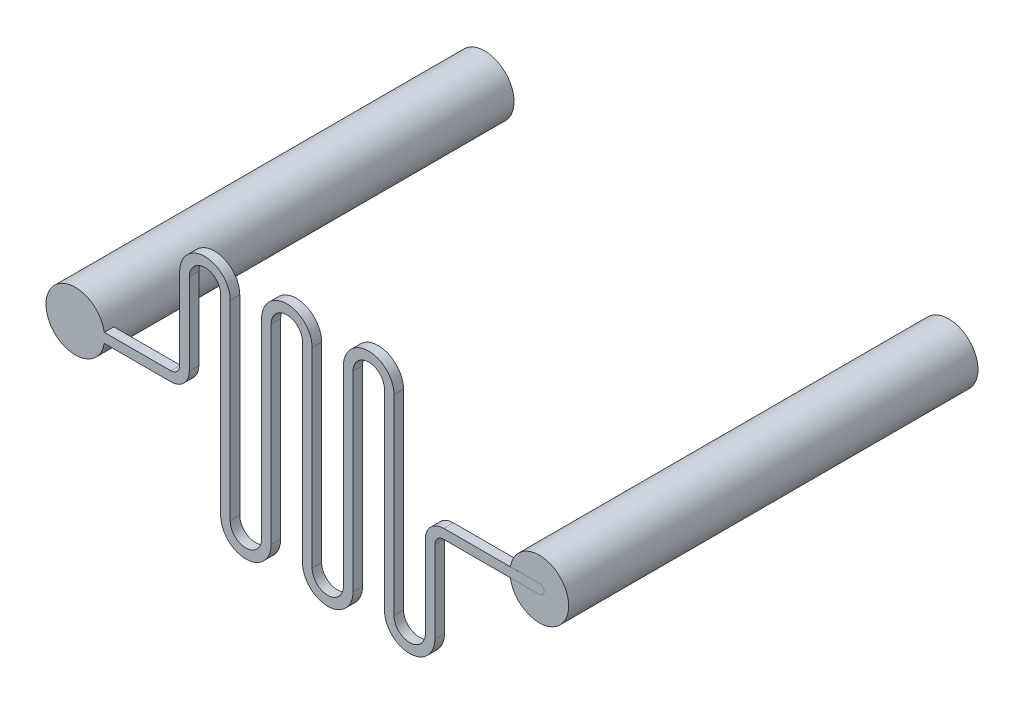
SolidWorks part; units mm, degrees
ref_plane "Front Plane" through (0, 0, 0) normal (0, 0, 1) x (1, 0, 0)
ref_plane "Top Plane" through (0, 0, 0) normal (0, 1, 0) x (1, 0, 0)
ref_plane "Right Plane" through (0, 0, 0) normal (1, 0, 0) x (0, 0, -1)
sketch "Sketch2" plane through (0, 0, 0) normal (0, 0, 1) x (1, 0, 0)
  line L3 (-20.5, -0.35) -> (-13.5, -0.35)
  line L6 (-12.15, 1) -> (-12.15, 7)
  line L9 (-9.85, 7) -> (-9.85, 0)
  line L12 (-9.85, 0) -> (-9.85, -7)
  line L15 (-6.15, -7) -> (-6.15, 0)
  line L18 (-6.15, 0) -> (-6.15, 7)
  line L21 (-3.85, 7) -> (-3.85, 0)
  line L22 (-3.85, 0) -> (-3.85, -7)
  line L23 (-0.15, -7) -> (-0.15, 0)
  line L24 (-0.15, 0) -> (-0.15, 7)
  line L25 (2.15, 7) -> (2.15, 0)
  line L26 (2.15, 0) -> (2.15, -7)
  line L27 (5.85, -7) -> (5.85, -1)
  line L28 (6.5, -0.35) -> (13.5, -0.35)
  line L29 (-20.5, 0.35) -> (-13.5, 0.35)
  line L30 (-12.85, 1) -> (-12.85, 7)
  line L31 (-9.15, 7) -> (-9.15, 0)
  line L32 (-9.15, 0) -> (-9.15, -7)
  line L33 (-6.85, -7) -> (-6.85, 0)
  line L34 (-6.85, 0) -> (-6.85, 7)
  line L35 (-3.15, 7) -> (-3.15, 0)
  line L36 (-3.15, 0) -> (-3.15, -7)
  line L37 (-0.85, -7) -> (-0.85, 0)
  line L38 (-0.85, 0) -> (-0.85, 7)
  line L39 (2.85, 7) -> (2.85, 0)
  line L40 (2.85, 0) -> (2.85, -7)
  line L41 (5.15, -7) -> (5.15, -1)
  line L42 (6.5, 0.35) -> (13.5, 0.35)
  arc A0 (13.5, -0.35) -> (13.5, 0.35) centre (13.5, 0) ccw
  arc A8 (-12.15, 1) -> (-13.5, -0.35) centre (-13.5, 1) cw
  arc A9 (-12.15, 7) -> (-9.85, 7) centre (-11, 7) cw
  arc A10 (-9.85, -7) -> (-6.15, -7) centre (-8, -7) ccw
  arc A11 (-6.15, 7) -> (-3.85, 7) centre (-5, 7) cw
  arc A12 (-3.85, -7) -> (-0.15, -7) centre (-2, -7) ccw
  arc A13 (-0.15, 7) -> (2.15, 7) centre (1, 7) cw
  arc A14 (2.15, -7) -> (5.85, -7) centre (4, -7) ccw
  arc A15 (5.85, -1) -> (6.5, -0.35) centre (6.5, -1) cw
  arc A16 (-12.85, 1) -> (-13.5, 0.35) centre (-13.5, 1) cw
  arc A17 (-12.85, 7) -> (-9.15, 7) centre (-11, 7) cw
  arc A18 (-9.15, -7) -> (-6.85, -7) centre (-8, -7) ccw
  arc A19 (-6.85, 7) -> (-3.15, 7) centre (-5, 7) cw
  arc A20 (-3.15, -7) -> (-0.85, -7) centre (-2, -7) ccw
  arc A21 (-0.85, 7) -> (2.85, 7) centre (1, 7) cw
  arc A22 (2.85, -7) -> (5.15, -7) centre (4, -7) ccw
  arc A23 (5.15, -1) -> (6.5, 0.35) centre (6.5, -1) cw
  arc A24 (-20.5, 0.35) -> (-20.5, -0.35) centre (-20.5, 0) ccw
  point P4 (0, 0)
  point P32 (5.5, 0)
  point P35 (-12.5, 0)
  dimension "D1" = 8
extrude "Boss-Extrude1" add sketch "Sketch2" along normal blind 0.7
ref_plane "Plane1" through (0, 0, 0) normal (0, 1, 0) x (1, 0, 0)
sketch "Sketch3" plane through (0, 0, 0) normal (0, 1, 0) x (1, 0, 0)
  line L0 (-20.5, -0.7) -> (-22.65, -0.7)
  line L2 (-20.5, -0.7) -> (-20.5, 29.3)
  line L3 (-20.5, 29.3) -> (-22.65, 29.3)
  line L4 (-22.65, 29.3) -> (-22.65, -0.7)
  dimension "D3" = 30
  dimension "D4" = 2.15
ref_plane "Plane2" through (0, 0, 0) normal (0, 1, 0) x (1, 0, 0)
sketch "Sketch4" plane through (0, 0, 0) normal (0, 1, 0) x (1, 0, 0)
  line L0 (13.5, -0.6996) -> (15.65, -0.6996)
  line L1 (13.5, -0.7) -> (13.5, 0) construction
  line L3 (13.5, -0.6996) -> (13.5, 29.3004)
  line L4 (13.5, 29.3004) -> (15.65, 29.3004)
  line L5 (15.65, 29.3004) -> (15.65, -0.6996)
  dimension "D3" = 30
  dimension "D4" = 2.15
revolve "Revolve1" add sketch "Sketch3" angle 360 about L2
revolve "Revolve2" add sketch "Sketch4" angle 360 about L3
sketch "Sketch5" plane through (0, 0, -29.3) normal (0, 0, -1) x (-1, 0, 0)
  circle A0 centre (-13.5, 0) radius 1.75
  circle A1 centre (20.5, 0) radius 1.75
  dimension "D1" = 3.5
  dimension "D2" = 3.5
extrude "Cut-Extrude1" cut sketch "Sketch5" against normal blind 29
